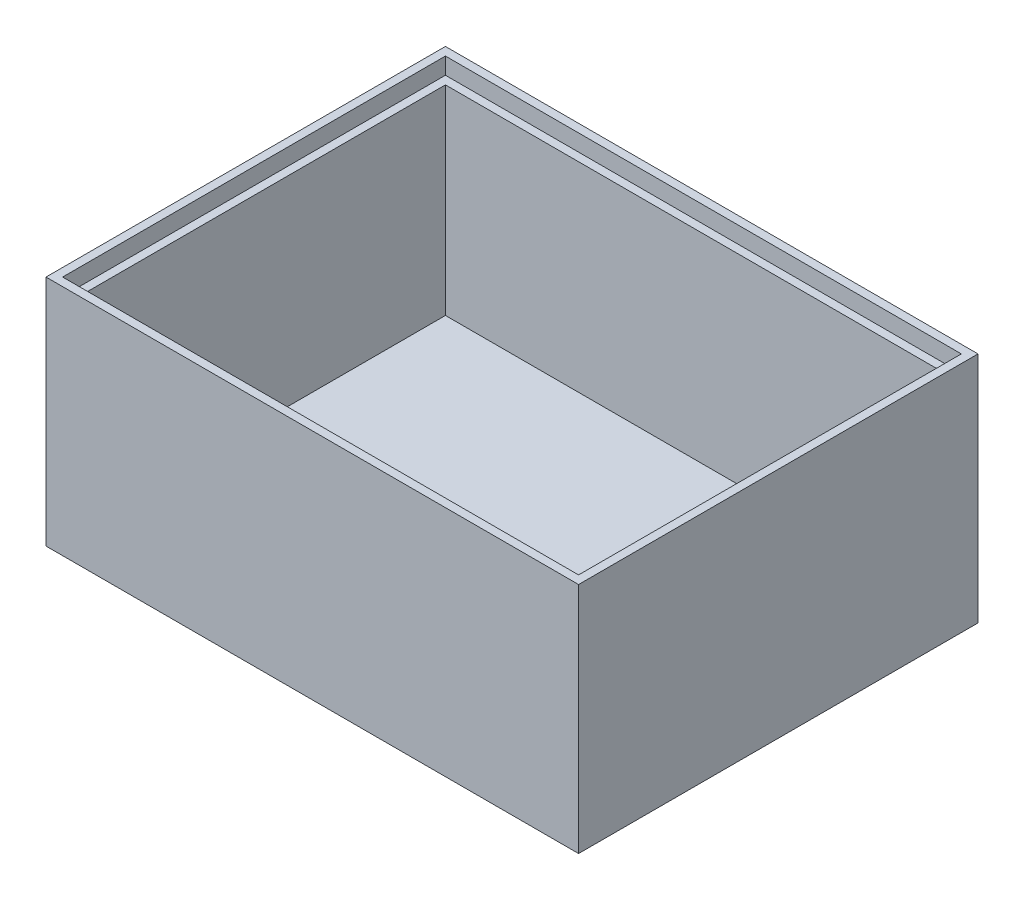
SolidWorks part; units mm, degrees
ref_plane "Front Plane" through (0, 0, 0) normal (0, 0, 1) x (1, 0, 0)
ref_plane "Top Plane" through (0, 0, 0) normal (0, 1, 0) x (1, 0, 0)
ref_plane "Right Plane" through (0, 0, 0) normal (1, 0, 0) x (0, 0, -1)
sketch "Sketch1" plane through (0, 0, 0) normal (0, 1, 0) x (1, 0, 0)
  line L1 (-101.6, -76.2) -> (101.6, -76.2)
  line L2 (-101.6, -76.2) -> (-101.6, 76.2)
  line L3 (-101.6, 76.2) -> (101.6, 76.2)
  line L4 (101.6, -76.2) -> (101.6, 76.2)
  line L5 (-101.6, -76.2) -> (101.6, 76.2) construction
  line L6 (-101.6, 76.2) -> (101.6, -76.2) construction
  point P0 (0, 0)
  dimension "D1" = 203.2
  dimension "D2" = 152.4
extrude "Boss-Extrude1" add sketch "Sketch1" along normal blind 6.35
sketch "Sketch2" plane through (0, 6.35, 0) normal (0, 1, 0) x (1, 0, 0)
  line L1 (-101.6, -76.2) -> (101.6, -76.2)
  line L2 (-101.6, -76.2) -> (-101.6, 76.2)
  line L3 (-101.6, 76.2) -> (101.6, 76.2)
  line L4 (101.6, -76.2) -> (101.6, 76.2)
  line L5 (-101.6, -76.2) -> (101.6, 76.2) construction
  line L6 (-101.6, 76.2) -> (101.6, -76.2) construction
  line L7 (-95.25, -69.85) -> (95.25, -69.85)
  line L8 (-95.25, -69.85) -> (-95.25, 69.85)
  line L9 (-95.25, 69.85) -> (95.25, 69.85)
  line L10 (95.25, -69.85) -> (95.25, 69.85)
  line L11 (-95.25, -69.85) -> (95.25, 69.85) construction
  line L12 (-95.25, 69.85) -> (95.25, -69.85) construction
  point P0 (0, 0)
  point P7 (0, 0)
  dimension "D1" = 6.35
  dimension "D2" = 6.35
extrude "Boss-Extrude2" add sketch "Sketch2" along normal blind 76.2
sketch "Sketch3" plane through (0, 82.55, 0) normal (0, 1, 0) x (1, 0, 0)
  line L0 (101.6, 76.2) -> (-101.6, 76.2) construction
  line L1 (-98.425, -73.025) -> (98.425, -73.025)
  line L2 (-98.425, -73.025) -> (-98.425, 73.025)
  line L3 (-98.425, 73.025) -> (98.425, 73.025)
  line L4 (98.425, -73.025) -> (98.425, 73.025)
  line L5 (-98.425, -73.025) -> (98.425, 73.025) construction
  line L6 (-98.425, 73.025) -> (98.425, -73.025) construction
  line L7 (101.6, -76.2) -> (101.6, 76.2) construction
  line L9 (-101.6, -76.2) -> (101.6, -76.2)
  line L10 (-101.6, -76.2) -> (-101.6, 76.2)
  line L11 (-101.6, 76.2) -> (101.6, 76.2)
  line L12 (101.6, -76.2) -> (101.6, 76.2)
  line L13 (-101.6, -76.2) -> (101.6, 76.2) construction
  line L14 (-101.6, 76.2) -> (101.6, -76.2) construction
  point P0 (0, 0)
  point P10 (0, 0)
  dimension "D1" = 3.175
  dimension "D2" = 3.175
extrude "Boss-Extrude3" add sketch "Sketch3" along normal blind 6.35
